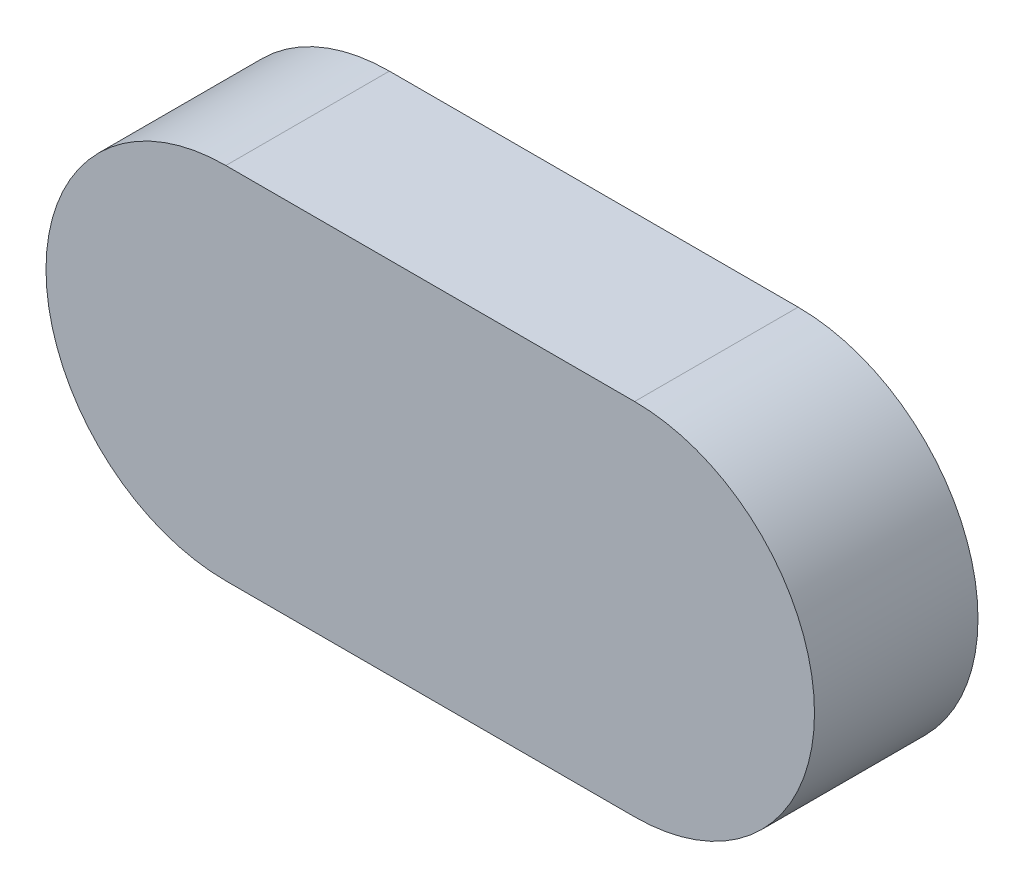
SolidWorks part; units mm, degrees
ref_plane "Front Plane" through (0, 0, 0) normal (0, 0, 1) x (1, 0, 0)
ref_plane "Top Plane" through (0, 0, 0) normal (0, 1, 0) x (1, 0, 0)
ref_plane "Right Plane" through (0, 0, 0) normal (1, 0, 0) x (0, 0, -1)
sketch "草图3" plane through (0, 0, 0) normal (0, 0, 1) x (1, 0, 0)
  line L0 (20, 50) -> (45, 50) construction
  line L1 (20, 61) -> (45, 61)
  line L2 (20, 39) -> (45, 39)
  arc A0 (20, 61) -> (20, 39) centre (20, 50) ccw
  arc A1 (45, 39) -> (45, 61) centre (45, 50) ccw
  point P2 (32.5, 50)
  point P7 (0, 0)
  dimension "width" = 22
  dimension "end1_x" = 20
  dimension "end2_x" = 45
  dimension "end1_y" = 50
extrude "CrankLink" add sketch "草图3" along normal blind 10
